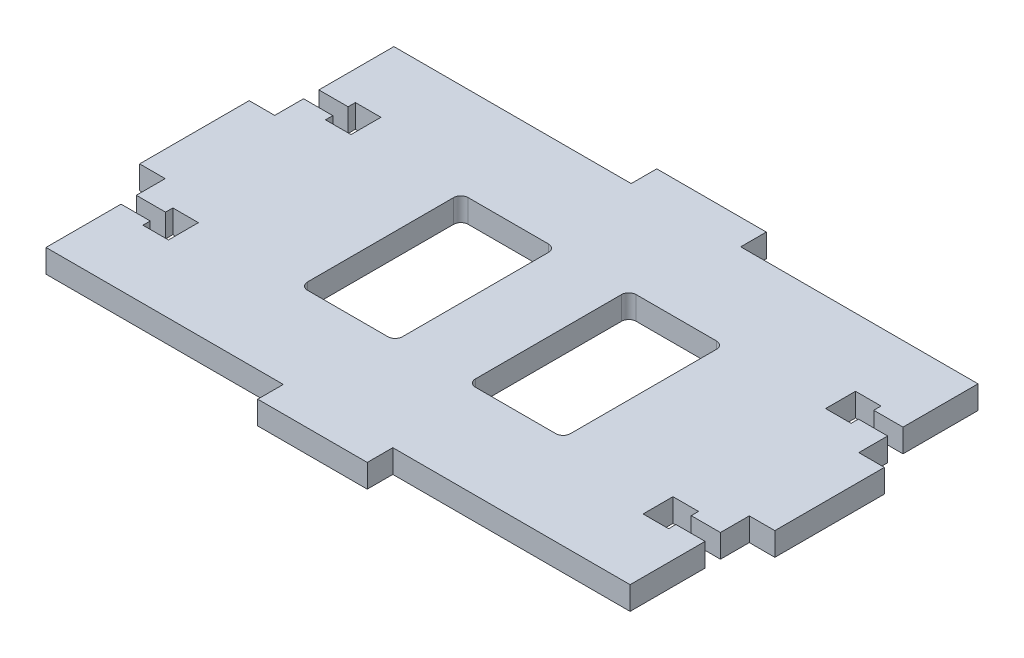
SolidWorks part; units mm, degrees
ref_plane "Front Plane" through (0, 0, 0) normal (0, 0, 1) x (1, 0, 0)
ref_plane "Top Plane" through (0, 0, 0) normal (0, 1, 0) x (1, 0, 0)
ref_plane "Right Plane" through (0, 0, 0) normal (1, 0, 0) x (0, 0, -1)
sketch "Sketch2" plane through (0, 0, 0) normal (0, 1, 0) x (1, 0, 0)
  line L0 (0, -1.7463) -> (0, 1.7463) construction
  line L1 (-40, 23.825) -> (40, 23.825)
  line L2 (-40, 23.825) -> (-40, -23.825)
  line L3 (-40, -23.825) -> (40, -23.825)
  line L4 (40, 23.825) -> (40, -23.825)
  point P4 (0, -23.825)
  dimension "D1" = 47.65
  dimension "D2" = 80
  dimension "D4" = 23.825
extrude "Boss-Extrude1" add sketch "Sketch2" along normal blind 3.175
sketch "Sketch3" plane through (0, 3.175, 0) normal (0, 1, 0) x (1, 0, 0)
  line L0 (40, 23.825) -> (-40, 23.825) construction
  line L1 (-7.5, 23.825) -> (7.5, 23.825)
  line L2 (-7.5, 23.825) -> (-7.5, 27.325)
  line L3 (-7.5, 27.325) -> (7.5, 27.325)
  line L4 (7.5, 23.825) -> (7.5, 27.325)
  point P6 (0, 23.825)
  dimension "D1" = 15
  dimension "D2" = 3.5
  dimension "D3" = 0
extrude "Boss-Extrude2" add sketch "Sketch3" against normal blind 3.175
sketch "Sketch4" plane through (0, 3.175, 0) normal (0, 1, 0) x (1, 0, 0)
  line L0 (-40, 23.825) -> (-40, -23.825) construction
  line L1 (-40, 7.5) -> (-43.5, 7.5)
  line L2 (-40, 7.5) -> (-40, -7.5)
  line L3 (-40, -7.5) -> (-43.5, -7.5)
  line L4 (-43.5, 7.5) -> (-43.5, -7.5)
  dimension "D1" = 15
  dimension "D2" = 3.5
  dimension "D3" = 7.5
extrude "Boss-Extrude3" add sketch "Sketch4" against normal blind 3.175
mirror "Mirror1" about plane through (0, 0, 0) normal (1, 0, 0) of "Boss-Extrude3"
mirror "Mirror2" about plane through (0, 0, 0) normal (0, 0, 1) of "Boss-Extrude2", "Mirror1"
sketch "Sketch5" plane through (0, 3.175, 0) normal (0, 1, 0) x (1, 0, 0)
  line L0 (-40, 13.55) -> (-36, 13.55)
  line L1 (-40, 23.825) -> (-40, 7.5) construction
  line L2 (-36, 13.55) -> (-36, 14.55)
  line L3 (-36, 14.55) -> (-32.5, 14.55)
  line L4 (-32.5, 14.55) -> (-32.5, 10.45)
  line L5 (-32.5, 10.45) -> (-36, 10.45)
  line L6 (-36, 10.45) -> (-36, 11.45)
  line L7 (-36, 11.45) -> (-40, 11.45)
  line L8 (-40, 11.45) -> (-40, 13.55)
  line L9 (-40, 7.5) -> (-43.5, 7.5) construction
  point P4 (-40, 12.5)
  dimension "D1" = 2.1
  dimension "D2" = 4.1
  dimension "D3" = 7.5
  dimension "D4" = 3.5
  dimension "D5" = 5
  dimension "D6" = 2.05
extrude "Cut-Extrude1" cut sketch "Sketch5" against normal blind 10
mirror "Mirror3" about plane through (0, 0, 0) normal (0, 0, 1) of "Cut-Extrude1"
mirror "Mirror4" about plane through (0, 0, 0) normal (1, 0, 0) of "Mirror3", "Cut-Extrude1"
sketch "Sketch6" plane through (0, 3.175, 0) normal (0, 1, 0) x (1, 0, 0)
  line L0 (0, -1.7463) -> (0, 1.7463) construction
  line L1 (5, 11) -> (18, 11)
  line L2 (5, 11) -> (5, -11)
  line L3 (5, -11) -> (18, -11)
  line L4 (18, 11) -> (18, -11)
  point P6 (18, 0)
  dimension "D1" = 13
  dimension "D2" = 22
  dimension "D3" = 5
  dimension "D4" = 0
extrude "Cut-Extrude2" cut sketch "Sketch6" against normal through all
fillet "Fillet1" radius 1 4 edges at (5, 1.5875, -11) (18, 1.5875, 11) (5, 1.5875, 11) (18, 1.5875, -11)
mirror "Mirror5" about plane through (0, 0, 0) normal (1, 0, 0) of "Fillet1", "Cut-Extrude2"
